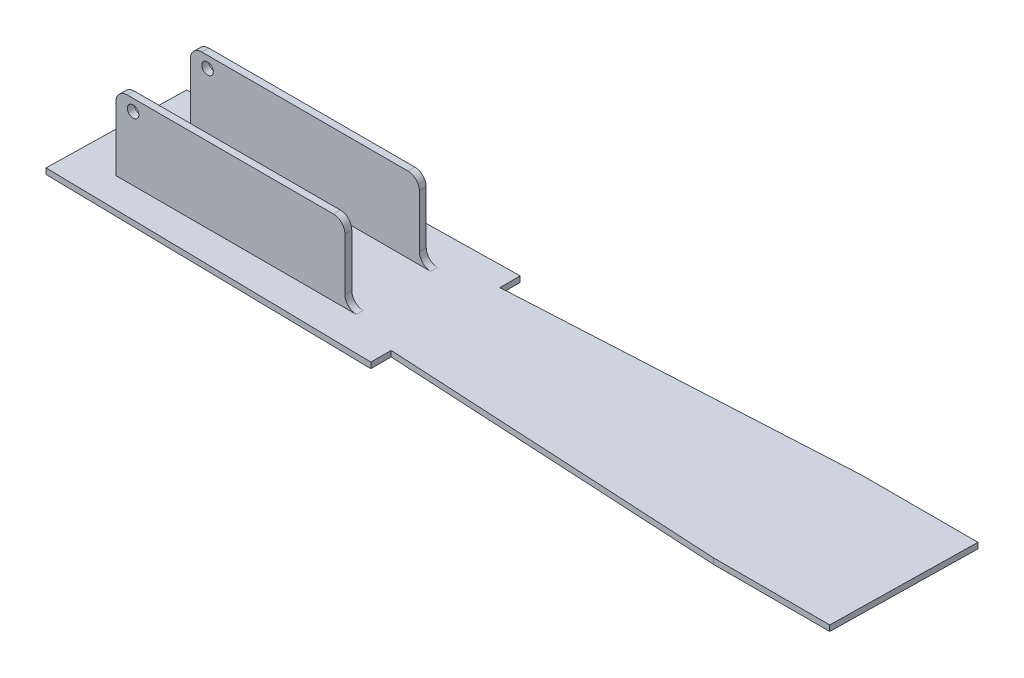
SolidWorks part; units mm, degrees
ref_plane "Front Plane" through (0, 0, 0) normal (0, 0, 1) x (1, 0, 0)
ref_plane "Top Plane" through (0, 0, 0) normal (0, 1, 0) x (1, 0, 0)
ref_plane "Right Plane" through (0, 0, 0) normal (1, 0, 0) x (0, 0, -1)
sketch "Sketch4" plane through (0, 0, 0) normal (0, 1, 0) x (1, 0, 0)
  line L0 (87.6673, 16.1607) -> (87.0936, -16.1607)
  line L1 (87.0936, -16.1607) -> (61.3164, -16.1607)
  line L2 (61.3164, -16.1607) -> (-14.31, -12.065)
  line L3 (-14.31, -12.065) -> (-14.31, -16.5701)
  line L4 (-14.31, -16.5701) -> (-87.6673, -15.2896)
  line L5 (-87.6673, -15.2896) -> (-87.0367, 15.3006)
  line L6 (-87.0367, 15.3006) -> (-14.31, 16.5701)
  line L7 (-14.31, 16.5701) -> (-14.31, 12.065)
  line L8 (-14.31, 12.065) -> (61.89, 16.1607)
  line L9 (61.89, 16.1607) -> (87.6673, 16.1607)
extrude "Boss-Extrude1" add sketch "Sketch4" along normal blind 1.27
sketch "Sketch5" plane through (0, 1.27, 0) normal (0, 1, 0) x (1, 0, 0)
  line L0 (-87.5222, -8.2495) -> (-87.1818, 8.2605) construction
  line L2 (-87.0367, 15.3006) -> (-87.6673, -15.2896) construction
  line L3 (-87.1818, 8.2605) -> (-78.4188, 8.2605) construction
  line L4 (-78.4188, 8.2605) -> (-27.6188, 8.2605) construction
  line L5 (136.4824, 0) -> (-136.4824, 0) construction
  line L6 (-78.4188, -7.4985) -> (-27.6188, -7.4985)
  line L7 (-78.4188, 9.0225) -> (-27.6188, 9.0225)
  line L8 (-78.4188, 9.0225) -> (-78.4188, 7.4985)
  line L9 (-78.4188, 7.4985) -> (-27.6188, 7.4985)
  line L10 (-27.6188, 9.0225) -> (-27.6188, 7.4985)
  line L11 (-78.4188, 9.0225) -> (-27.6188, 7.4985) construction
  line L12 (-78.4188, 7.4985) -> (-27.6188, 9.0225) construction
  line L13 (-27.6188, -9.0225) -> (-27.6188, -7.4985)
  line L14 (-78.4188, -9.0225) -> (-27.6188, -9.0225)
  line L15 (-78.4188, -9.0225) -> (-78.4188, -7.4985)
  point P0 (-53.0188, 8.2605)
  point P6 (-87.352, 0.0055)
  point P13 (0, 0)
  dimension "D1" = 16.51
  dimension "D2" = 50.8
  dimension "D3" = 8.763
  dimension "D4" = 1.524
extrude "Boss-Extrude2" add sketch "Sketch5" along normal blind 16.764
sketch "Sketch6" plane through (0, 0, 9.0225) normal (0, 0, 1) x (1, 0, 0)
  line L0 (-78.4188, 18.034) -> (-78.4188, 15.494) construction
  line L1 (-78.4188, 18.034) -> (-78.4188, 1.27) construction
  line L2 (-78.4188, 15.494) -> (-74.6088, 15.494) construction
  circle A0 centre (-74.6088, 15.494) radius 1.27
  dimension "D3" = 2.54
  dimension "D1" = 3.81
  dimension "D2" = 2.54
extrude "Cut-Extrude1" cut sketch "Sketch6" against normal blind 19.304
fillet "Fillet1" radius 2.54 6 edges at (-27.6188, 1.27, -8.2605) (-27.6188, 1.27, 8.2605) (-78.4188, 18.034, -8.2605) (-78.4188, 18.034, 8.2605) (-27.6188, 18.034, -8.2605) (-27.6188, 18.034, 8.2605)
sketch "Sketch7" plane through (0, 1.27, 0) normal (0, 1, 0) x (1, 0, 0)
  line L0 (-87.352, 0.0055) -> (-58.142, 0.0055) construction
  line L1 (-87.0367, 15.3006) -> (-87.6673, -15.2896) construction
  circle A0 centre (-58.142, 0.0055) radius 1.27
  dimension "D2" = 2.54
  dimension "D1" = 29.21
extrude "Cut-Extrude2" cut sketch "Sketch7" against normal blind 19.304
